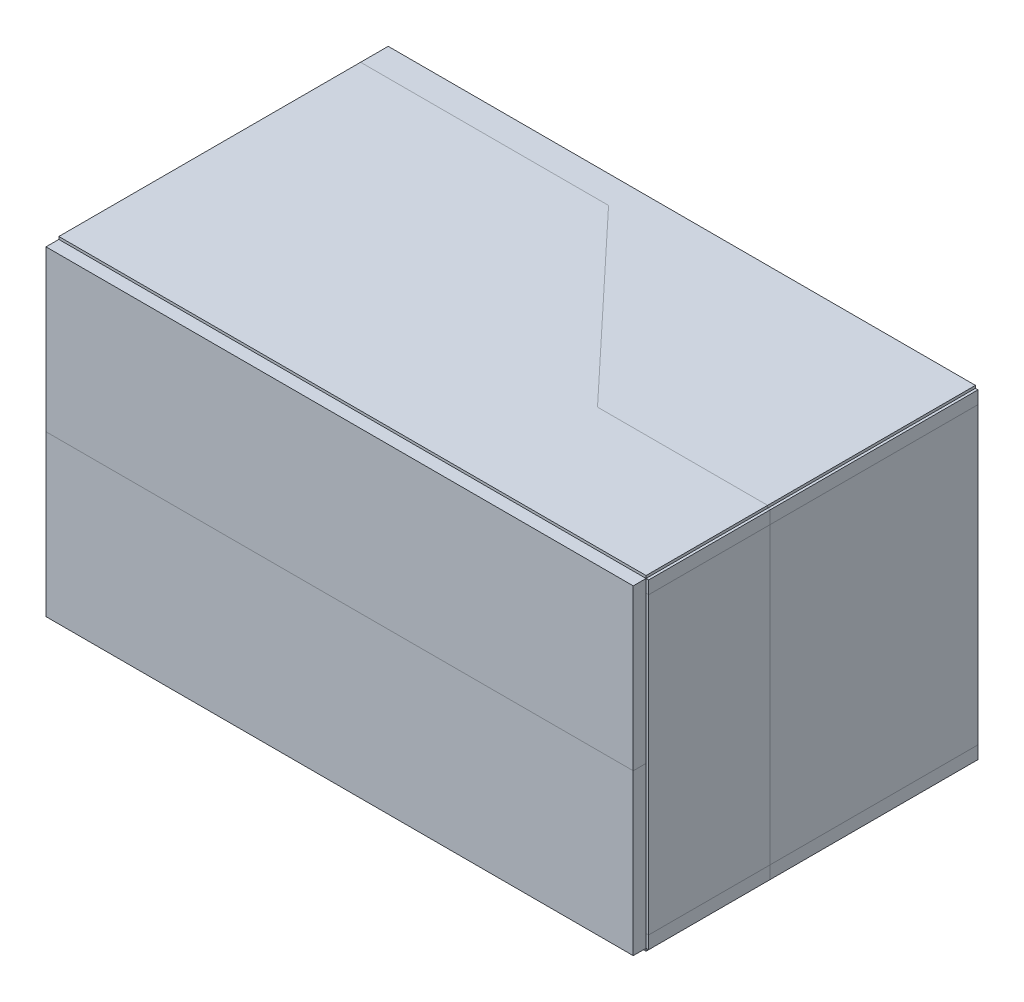
SolidWorks part; units mm, degrees
other "후면"
other "천장2"
other "천장1"
other "좌측면"
other "정면"
other "우측면"
other "바닥"
other "후면하단작음2"
other "후면상단작음2"
other "상단인테리어2"
other "하단인테리어2"
other "후면하단큼1"
other "후면상단큼1"
other "후면하단작음1"
other "후면상단작음1"
other "상단인테리어1"
other "하단인테리어1"
other "에어컨"
ref_plane "정면" through (0, 0, 0) normal (0, 0, 1) x (1, 0, 0)
ref_plane "윗면" through (0, 0, 0) normal (0, 1, 0) x (1, 0, 0)
ref_plane "우측면" through (0, 0, 0) normal (1, 0, 0) x (0, 0, -1)
sketch "스케치1" plane through (0, 0, 0) normal (0, 0, 1) x (1, 0, 0)
  line L1 (51, 74.896) -> (280, 74.896)
  line L2 (51, 74.896) -> (51, -50)
  line L3 (51, -50) -> (280, -50)
  line L4 (280, 74.896) -> (280, -50)
extrude "보스-돌출1" add sketch "스케치1" along normal up to surface (7.8606 mm away)
sketch "스케치2" plane through (0, 0, 7.8606) normal (0, 0, 1) x (1, 0, 0)
  line L0 (280, 74.896) -> (280, -50) construction
  line L1 (51, 74.896) -> (280, 74.896)
  line L2 (51, 74.896) -> (51, 69.896)
  line L3 (51, 69.896) -> (280, 69.896)
  line L4 (280, 74.896) -> (280, 69.896)
  dimension "D1" = 5
extrude "컷-돌출1" cut sketch "스케치2" against normal up to surface (7.8606 mm away) contours L1 L3 L2 up to face at (165.5, 12.448, 0)
sketch "스케치4" plane through (0, 0, 7.8606) normal (0, 0, 1) x (1, 0, 0)
  line L0 (280, 69.896) -> (280, -50) construction
  line L1 (51, -50) -> (280, -50)
  line L2 (51, -50) -> (51, -45)
  line L3 (51, -45) -> (280, -45)
  line L4 (280, -50) -> (280, -45)
  line M1 (280, -50) -> (280, 69.896)
  line M3 (51, 69.896) -> (51, -50)
  line M4 (51, -50) -> (280, -50)
  dimension "D1" = 5
extrude "컷-돌출2" cut sketch "스케치4" against normal up to surface (7.8606 mm away) contours L3 M3 M4 M1 up to face at (165.5, 9.948, 0)
sketch "스케치5" plane through (0, 0, 7.8606) normal (0, 0, 1) x (1, 0, 0)
  line L0 (51, -45) -> (280, -45) construction
  line L1 (280, 69.896) -> (275, 69.896)
  line L2 (280, 69.896) -> (280, -45)
  line L3 (280, -45) -> (275, -45)
  line L4 (275, 69.896) -> (275, -45)
  line M1 (51, -45) -> (280, -45)
  line M2 (280, -45) -> (280, 69.896)
  line M3 (280, 69.896) -> (51, 69.896)
  dimension "D1" = 5
extrude "컷-돌출3" cut sketch "스케치5" against normal up to surface (7.8606 mm away) contours L4 M3 M1 M2 up to face at (165.5, 12.448, 0)
sketch "스케치6" plane through (0, 69.896, 0) normal (0, 1, 0) x (1, 0, 0)
  line L1 (51, 0) -> (280, 0)
  line L2 (51, 0) -> (51, -128.4421)
  line L3 (51, -128.4421) -> (280, -128.4421)
  line L4 (280, 0) -> (280, -128.4421)
extrude "보스-돌출3" add sketch "스케치6" along normal blind 5 separate body
sketch "스케치7" plane through (0, 0, 7.8606) normal (0, 0, 1) x (1, 0, 0)
  line L0 (51, -45) -> (275, -45) construction
  line L1 (51, 69.896) -> (56, 69.896)
  line L2 (51, 69.896) -> (51, -45)
  line L3 (51, -45) -> (56, -45)
  line L4 (56, 69.896) -> (56, -45)
  dimension "D1" = 5
extrude "보스-돌출4" add sketch "스케치7" along normal up to surface (120.5815 mm away) separate body up to face at (165.5, 72.396, 128.4421)
sketch "스케치8" plane through (0, -45, 0) normal (0, -1, 0) x (1, 0, 0)
  line L1 (51, 128.4421) -> (280, 128.4421)
  line L2 (51, 128.4421) -> (51, 0)
  line L3 (51, 0) -> (280, 0)
  line L4 (280, 128.4421) -> (280, 0)
extrude "보스-돌출5" add sketch "스케치8" along normal blind 5 separate body
sketch "스케치9" plane through (0, 0, 128.4421) normal (0, 0, 1) x (1, 0, 0)
  line L1 (51, 74.896) -> (280, 74.896)
  line L2 (51, 74.896) -> (51, 12.446)
  line L3 (51, 12.446) -> (280, 12.446)
  line L4 (280, 74.896) -> (280, 12.446)
  dimension "D1" = 62.45
extrude "보스-돌출6" add sketch "스케치9" along normal blind 5 separate body
sketch "스케치10" plane through (0, 0, 128.4421) normal (0, 0, 1) x (1, 0, 0)
  line L1 (51, 12.446) -> (280, 12.446)
  line L2 (51, 12.446) -> (51, -50)
  line L3 (51, -50) -> (280, -50)
  line L4 (280, 12.446) -> (280, -50)
extrude "보스-돌출7" add sketch "스케치10" along normal blind 5 separate body
sketch "스케치11" plane through (275, 0, 0) normal (1, 0, 0) x (0, 0, -1)
  line L1 (0, -45) -> (-128.4421, -45)
  line L2 (0, -45) -> (0, 69.896)
  line L3 (0, 69.896) -> (-128.4421, 69.896)
  line L4 (-128.4421, -45) -> (-128.4421, 69.896)
extrude "보스-돌출8" add sketch "스케치11" along normal blind 5 separate body
sketch "스케치12" plane through (0, -50, 0) normal (0, -1, 0) x (1, 0, 0)
  line L0 (51, 10.7712) -> (147.7059, 10.7712)
  line L1 (51, 128.4421) -> (51, 0) construction
  line L2 (147.7059, 10.7712) -> (213.6585, 81.0356)
  line L3 (213.6585, 81.0356) -> (280, 81.0356)
  line L4 (280, 0) -> (280, 128.4421) construction
  line L5 (51, 10.7712) -> (51, 0)
  line L6 (51, 0) -> (280, 0)
  line L7 (280, 0) -> (280, 81.0356)
extrude "보스-돌출9" add sketch "스케치12" along normal blind 1 separate body
sketch "스케치13" plane through (0, -50, 0) normal (0, -1, 0) x (1, 0, 0)
  line L0 (51, 128.4421) -> (51, 10.7712)
  line L1 (51, 10.7712) -> (147.7059, 10.7712)
  line L2 (147.7059, 10.7712) -> (213.6585, 81.0356)
  line L3 (213.6585, 81.0356) -> (280, 81.0356)
  line L4 (280, 81.0356) -> (280, 128.4421)
  line L5 (280, 128.4421) -> (51, 128.4421)
extrude "보스-돌출10" add sketch "스케치13" along normal blind 1 separate body
sketch "스케치14" plane through (280, 0, 0) normal (1, 0, 0) x (0, 0, -1)
  line L1 (-81.0356, -50) -> (-128.4421, -50)
  line L2 (-81.0356, -50) -> (-81.0356, -45)
  line L3 (-81.0356, -45) -> (-128.4421, -45)
  line L4 (-128.4421, -50) -> (-128.4421, -45)
extrude "보스-돌출11" add sketch "스케치14" along normal blind 1 separate body
sketch "스케치15" plane through (280, 0, 0) normal (1, 0, 0) x (0, 0, -1)
  line L1 (-81.0356, -50) -> (0, -50)
  line L2 (-81.0356, -50) -> (-81.0356, -45)
  line L3 (-81.0356, -45) -> (0, -45)
  line L4 (0, -50) -> (0, -45)
extrude "보스-돌출12" add sketch "스케치15" along normal blind 1 separate body
sketch "스케치16" plane through (280, 0, 0) normal (1, 0, 0) x (0, 0, -1)
  line L0 (-128.4421, 69.896) -> (0, 69.896) construction
  line L1 (-128.4421, -45) -> (-81.0356, -45)
  line L2 (-128.4421, -45) -> (-128.4421, 69.896)
  line L3 (-128.4421, 69.896) -> (-81.0356, 69.896)
  line L4 (-81.0356, -45) -> (-81.0356, 69.896)
extrude "보스-돌출13" add sketch "스케치16" along normal blind 1 separate body
sketch "스케치17" plane through (280, 0, 0) normal (1, 0, 0) x (0, 0, -1)
  line L0 (0, 74.896) -> (0, 69.896) construction
  line L1 (-81.0356, -45) -> (0, -45)
  line L2 (-81.0356, -45) -> (-81.0356, 69.896)
  line L3 (-81.0356, 69.896) -> (0, 69.896)
  line L4 (0, -45) -> (0, 69.896)
  line L5 (-128.4421, 69.896) -> (0, 69.896) construction
extrude "보스-돌출14" add sketch "스케치17" along normal blind 1 separate body
ref_plane "평면1" through (0, 12.446, 0) normal (0, 1, 0) x (1, 0, 0)
mirror "대칭 복사2" about plane through (0, 12.446, 0) normal (0, 1, 0) of bodies 112 113 114 115
other "바디 저장1"
other "바디 저장2"
sketch "스케치18" plane through (0, 0, 7.8606) normal (0, 0, 1) x (1, 0, 0)
  line L0 (51, 69.896) -> (275, 69.896) construction
  line L1 (56, 69.896) -> (109.127, 69.896)
  line L2 (56, 69.896) -> (56, 46.8524)
  line L3 (56, 46.8524) -> (109.127, 46.8524)
  line L4 (109.127, 69.896) -> (109.127, 46.8524)
  line L5 (118.0366, 69.896) -> (158.4268, 69.896)
  line L6 (118.0366, 69.896) -> (118.0366, 46.8524)
  line L7 (118.0366, 46.8524) -> (158.4268, 46.8524)
  line L8 (158.4268, 69.896) -> (158.4268, 46.8524)
  line L9 (51, 69.896) -> (280, 69.896) construction
  line L10 (165.5, 69.896) -> (199.5595, 69.896)
  line L11 (165.5, 69.896) -> (165.5, 46.8524)
  line L12 (165.5, 46.8524) -> (199.5595, 46.8524)
  line L13 (199.5595, 69.896) -> (199.5595, 46.8524)
  line L14 (56, 69.896) -> (56, -45) construction
  line L15 (206.8357, 69.896) -> (247.9684, 69.896)
  line L16 (206.8357, 69.896) -> (206.8357, 46.8524)
  line L17 (206.8357, 46.8524) -> (247.9684, 46.8524)
  line L18 (247.9684, 69.896) -> (247.9684, 46.8524)
  line L19 (56, 39.2792) -> (90.5653, 39.2792)
  line L20 (56, 39.2792) -> (56, 12.448)
  line L21 (56, 12.448) -> (90.5653, 12.448)
  line L22 (90.5653, 39.2792) -> (90.5653, 12.448)
  line L24 (95.7626, 39.2792) -> (126.9462, 39.2792)
  line L25 (95.7626, 39.2792) -> (95.7626, 12.448)
  line L26 (95.7626, 12.448) -> (126.9462, 12.448)
  line L27 (126.9462, 39.2792) -> (126.9462, 12.448)
  line L28 (135.8558, 39.2792) -> (184.2647, 39.2792)
  line L29 (135.8558, 39.2792) -> (135.8558, -2.7445)
  line L30 (135.8558, -2.7445) -> (184.2647, -2.7445)
  line L31 (184.2647, 39.2792) -> (184.2647, -2.7445)
  line L32 (189.462, 39.2792) -> (199.5595, 39.2792)
  line L33 (189.462, 39.2792) -> (189.462, 27.2512)
  line L34 (189.462, 27.2512) -> (199.5595, 27.2512)
  line L35 (199.5595, 39.2792) -> (199.5595, 27.2512)
  line L36 (206.8357, 39.2792) -> (263.5602, 39.2792)
  line L37 (206.8357, 39.2792) -> (206.8357, 13.4413)
  line L38 (206.8357, 13.4413) -> (263.5602, 13.4413)
  line L39 (263.5602, 39.2792) -> (263.5602, 13.4413)
  line L40 (56, 3.9377) -> (126.9462, 3.9377)
  line L41 (56, 3.9377) -> (56, -20.5637)
  line L42 (56, -20.5637) -> (126.9462, -20.5637)
  line L43 (126.9462, 3.9377) -> (126.9462, -20.5637)
  line L44 (130.2131, -5.1204) -> (194.5108, -5.1204)
  line L45 (130.2131, -5.1204) -> (130.2131, -31.8492)
  line L46 (130.2131, -31.8492) -> (194.5108, -31.8492)
  line L47 (194.5108, -5.1204) -> (194.5108, -31.8492)
  line L48 (187.977, 11.0654) -> (263.5602, 11.0654)
  line L49 (187.977, 11.0654) -> (187.977, -2.7445)
  line L50 (187.977, -2.7445) -> (263.5602, -2.7445)
  line L51 (263.5602, 11.0654) -> (263.5602, -2.7445)
  line L52 (199.5595, -7.1993) -> (263.5602, -7.1993)
  line L53 (199.5595, -7.1993) -> (199.5595, -41.5013)
  line L54 (199.5595, -41.5013) -> (263.5602, -41.5013)
  line L55 (263.5602, -7.1993) -> (263.5602, -41.5013)
  line L56 (58.6392, -27.8399) -> (81.5072, -27.8399)
  line L57 (58.6392, -27.8399) -> (58.6392, -41.5013)
  line L58 (58.6392, -41.5013) -> (81.5072, -41.5013)
  line L59 (81.5072, -27.8399) -> (81.5072, -41.5013)
  line L60 (97.2475, -29.9188) -> (121.4519, -29.9188)
  line L61 (97.2475, -29.9188) -> (97.2475, -41.5013)
  line L62 (97.2475, -41.5013) -> (121.4519, -41.5013)
  line L63 (121.4519, -29.9188) -> (121.4519, -41.5013)
extrude "보스-돌출15" add sketch "스케치18" along normal blind 20 separate body
sketch "스케치19" plane through (0, 0, 27.8606) normal (0, 0, 1) x (1, 0, 0)
  line L0 (206.8357, 69.896) -> (206.8357, 46.8524) construction
  line L1 (59.7235, 66.6576) -> (101.2833, 66.6576)
  line L2 (59.7235, 66.6576) -> (59.7235, 34.1197)
  line L3 (59.7235, 34.1197) -> (101.2833, 34.1197)
  line L4 (101.2833, 66.6576) -> (101.2833, 34.1197)
  line L5 (107.7908, 64.8828) -> (163.8448, 64.8828)
  line L6 (107.7908, 64.8828) -> (107.7908, 39.2962)
  line L7 (107.7908, 39.2962) -> (163.8448, 39.2962)
  line L8 (163.8448, 64.8828) -> (163.8448, 39.2962)
  line L9 (173.9019, 63.6996) -> (194.6079, 63.6996)
  line L10 (173.9019, 63.6996) -> (173.9019, 22.1398)
  line L11 (173.9019, 22.1398) -> (194.6079, 22.1398)
  line L12 (194.6079, 63.6996) -> (194.6079, 22.1398)
  line L13 (206.8357, 66.6576) -> (254.3593, 66.6576)
  line L14 (206.8357, 66.6576) -> (206.8357, 32.4928)
  line L15 (206.8357, 32.4928) -> (254.3593, 32.4928)
  line L16 (254.3593, 66.6576) -> (254.3593, 32.4928)
  line L17 (58.6392, -41.5013) -> (81.5072, -41.5013) construction
  line L18 (66.379, 25.9852) -> (133.0817, 25.9852)
  line L19 (66.379, 25.9852) -> (66.379, -6.8485)
  line L20 (66.379, -6.8485) -> (133.0817, -6.8485)
  line L21 (133.0817, 25.9852) -> (133.0817, -6.8485)
  line L22 (148.6111, 18.2944) -> (189.7272, 18.2944)
  line L23 (148.6111, 18.2944) -> (148.6111, -28.8855)
  line L24 (148.6111, -28.8855) -> (189.7272, -28.8855)
  line L25 (189.7272, 18.2944) -> (189.7272, -28.8855)
  line L26 (201.5592, 21.1045) -> (258.5005, 21.1045)
  line L27 (201.5592, 21.1045) -> (201.5592, -32.8788)
  line L28 (201.5592, -32.8788) -> (258.5005, -32.8788)
  line L29 (258.5005, 21.1045) -> (258.5005, -32.8788)
  line L30 (133.0817, -14.5393) -> (64.4563, -14.5393)
  line L31 (133.0817, -14.5393) -> (133.0817, -41.5013)
  line L32 (133.0817, -41.5013) -> (64.4563, -41.5013)
  line L33 (64.4563, -14.5393) -> (64.4563, -41.5013)
extrude "보스-돌출16" add sketch "스케치19" along normal blind 20 separate body
sketch "스케치20" plane through (0, 0, 47.8606) normal (0, 0, 1) x (1, 0, 0)
  line L0 (184.2647, -2.7445) -> (184.2647, 39.2792) construction
  line L1 (70.0732, 56.5044) -> (115.3637, 56.5044)
  line L2 (70.0732, 56.5044) -> (70.0732, 11.3624)
  line L3 (70.0732, 11.3624) -> (115.3637, 11.3624)
  line L4 (115.3637, 56.5044) -> (115.3637, 11.3624)
  line L5 (121.0065, 67.6415) -> (180.5524, 67.6415)
  line L6 (121.0065, 67.6415) -> (121.0065, 15.3717)
  line L7 (121.0065, 15.3717) -> (180.5524, 15.3717)
  line L8 (180.5524, 67.6415) -> (180.5524, 15.3717)
  line L9 (186.1951, 67.6415) -> (240.6922, 67.6415)
  line L10 (186.1951, 67.6415) -> (186.1951, 39.5762)
  line L11 (186.1951, 39.5762) -> (240.6922, 39.5762)
  line L12 (240.6922, 67.6415) -> (240.6922, 39.5762)
  line L13 (245.8895, 67.6415) -> (269.0545, 67.6415)
  line L14 (245.8895, 67.6415) -> (245.8895, 10.1745)
  line L15 (245.8895, 10.1745) -> (269.0545, 10.1745)
  line L16 (269.0545, 67.6415) -> (269.0545, 10.1745)
  line L17 (61.609, 2.1558) -> (117.4426, 2.1558)
  line L18 (61.609, 2.1558) -> (61.609, -35.2646)
  line L19 (61.609, -35.2646) -> (117.4426, -35.2646)
  line L20 (117.4426, 2.1558) -> (117.4426, -35.2646)
  line L21 (123.0854, 6.9076) -> (176.84, 6.9076)
  line L22 (123.0854, 6.9076) -> (123.0854, -36.601)
  line L23 (123.0854, -36.601) -> (176.84, -36.601)
  line L24 (176.84, 6.9076) -> (176.84, -36.601)
  line L25 (184.2647, 29.0331) -> (204.1628, 29.0331)
  line L26 (184.2647, 29.0331) -> (184.2647, -35.2646)
  line L27 (184.2647, -35.2646) -> (204.1628, -35.2646)
  line L28 (204.1628, 29.0331) -> (204.1628, -35.2646)
  line L30 (212.1815, 26.0633) -> (235.9405, 26.0633)
  line L31 (212.1815, 26.0633) -> (212.1815, -36.601)
  line L32 (212.1815, -36.601) -> (235.9405, -36.601)
  line L33 (235.9405, 26.0633) -> (235.9405, -36.601)
  line L34 (243.2166, -5.2689) -> (272.7668, -5.2689)
  line L35 (243.2166, -5.2689) -> (243.2166, -36.601)
  line L36 (243.2166, -36.601) -> (272.7668, -36.601)
  line L37 (272.7668, -5.2689) -> (272.7668, -36.601)
extrude "보스-돌출17" add sketch "스케치20" along normal blind 30 separate body
sketch "스케치21" plane through (0, 0, 77.8606) normal (0, 0, 1) x (1, 0, 0)
  line L0 (61.609, -35.2646) -> (117.4426, -35.2646) construction
  line L1 (58.6392, 67.6415) -> (83.1406, 67.6415)
  line L2 (58.6392, 67.6415) -> (58.6392, 41.8036)
  line L3 (58.6392, 41.8036) -> (83.1406, 41.8036)
  line L4 (83.1406, 67.6415) -> (83.1406, 41.8036)
  line L5 (59.8271, 29.4786) -> (95.4656, 29.4786)
  line L6 (59.8271, 29.4786) -> (59.8271, -4.0809)
  line L7 (59.8271, -4.0809) -> (95.4656, -4.0809)
  line L8 (95.4656, 29.4786) -> (95.4656, -4.0809)
  line L9 (93.6837, 63.9291) -> (136.8953, 63.9291)
  line L10 (93.6837, 63.9291) -> (93.6837, 32.894)
  line L11 (93.6837, 32.894) -> (136.8953, 32.894)
  line L12 (136.8953, 63.9291) -> (136.8953, 32.894)
  line L13 (109.8694, 23.2419) -> (150.7052, 23.2419)
  line L14 (109.8694, 23.2419) -> (109.8694, -19.8212)
  line L15 (109.8694, -19.8212) -> (150.7052, -19.8212)
  line L16 (150.7052, 23.2419) -> (150.7052, -19.8212)
  line L17 (58.6392, -15.0694) -> (105.7116, -15.0694)
  line L18 (58.6392, -15.0694) -> (58.6392, -35.2646)
  line L19 (58.6392, -35.2646) -> (105.7116, -35.2646)
  line L20 (105.7116, -15.0694) -> (105.7116, -35.2646)
  line L22 (155.16, 59.4743) -> (193.9168, 59.4743)
  line L23 (155.16, 59.4743) -> (155.16, 12.6989)
  line L24 (155.16, 12.6989) -> (193.9168, 12.6989)
  line L25 (193.9168, 59.4743) -> (193.9168, 12.6989)
  line L26 (206.6872, 61.9987) -> (262.6693, 61.9987)
  line L27 (206.6872, 61.9987) -> (206.6872, 29.4786)
  line L28 (206.6872, 29.4786) -> (262.6693, 29.4786)
  line L29 (262.6693, 61.9987) -> (262.6693, 29.4786)
extrude "보스-돌출18" add sketch "스케치21" along normal blind 30 separate body
sketch "스케치22" plane through (56, 0, 0) normal (1, 0, 0) x (0, 0, -1)
  line L0 (-128.4421, 12.448) -> (-85.2902, 12.448) construction
  line L1 (-128.4421, 69.896) -> (-128.4421, -45) construction
  line L3 (-108.4421, 52.448) -> (-128.4421, 52.448)
  line L4 (-108.4421, 52.448) -> (-108.4421, -27.552)
  line L5 (-108.4421, -27.552) -> (-128.4421, -27.552)
  line L6 (-128.4421, 52.448) -> (-128.4421, -27.552)
  line L7 (-108.4421, 52.448) -> (-128.4421, -27.552) construction
  line L8 (-108.4421, -27.552) -> (-128.4421, 52.448) construction
  point P4 (-118.4421, 12.448)
  dimension "D1" = 20
  dimension "D2" = 80
extrude "보스-돌출19" add sketch "스케치22" along normal blind 20 separate body
fillet "필렛1" radius 10 1 edges at (76, 12.448, 108.4421)
sketch "스케치23" plane through (0, 0, 128.4421) normal (0, 0, 1) x (1, 0, 0)
  line L0 (76, -27.552) -> (56, -27.552) construction
  line L1 (57.2078, 47.448) -> (59.2078, 47.448)
  line L2 (57.2078, 47.448) -> (57.2078, -22.552)
  line L3 (57.2078, -22.552) -> (59.2078, -22.552)
  line L4 (59.2078, 47.448) -> (59.2078, -22.552)
  line L5 (76, 52.448) -> (56, 52.448) construction
  line L6 (62.2078, 47.448) -> (62.2078, -22.552)
  line L7 (60.2078, 47.448) -> (62.2078, 47.448)
  line L8 (60.2078, 47.448) -> (60.2078, -22.552)
  line L9 (60.2078, -22.552) -> (62.2078, -22.552)
  line L10 (65.2078, 47.448) -> (65.2078, -22.552)
  line L11 (63.2078, 47.448) -> (65.2078, 47.448)
  line L12 (63.2078, 47.448) -> (63.2078, -22.552)
  line L13 (63.2078, -22.552) -> (65.2078, -22.552)
  line L14 (68.2078, 47.448) -> (68.2078, -22.552)
  line L15 (66.2078, 47.448) -> (68.2078, 47.448)
  line L16 (66.2078, 47.448) -> (66.2078, -22.552)
  line L17 (66.2078, -22.552) -> (68.2078, -22.552)
  line L18 (71.2078, 47.448) -> (71.2078, -22.552)
  line L19 (69.2078, 47.448) -> (71.2078, 47.448)
  line L20 (69.2078, 47.448) -> (69.2078, -22.552)
  line L21 (69.2078, -22.552) -> (71.2078, -22.552)
  dimension "D1" = 2
  dimension "D2" = 5
  dimension "D3" = 5
  dimension "D4" = 5
extrude "컷-돌출4" cut sketch "스케치23" against normal blind 15
